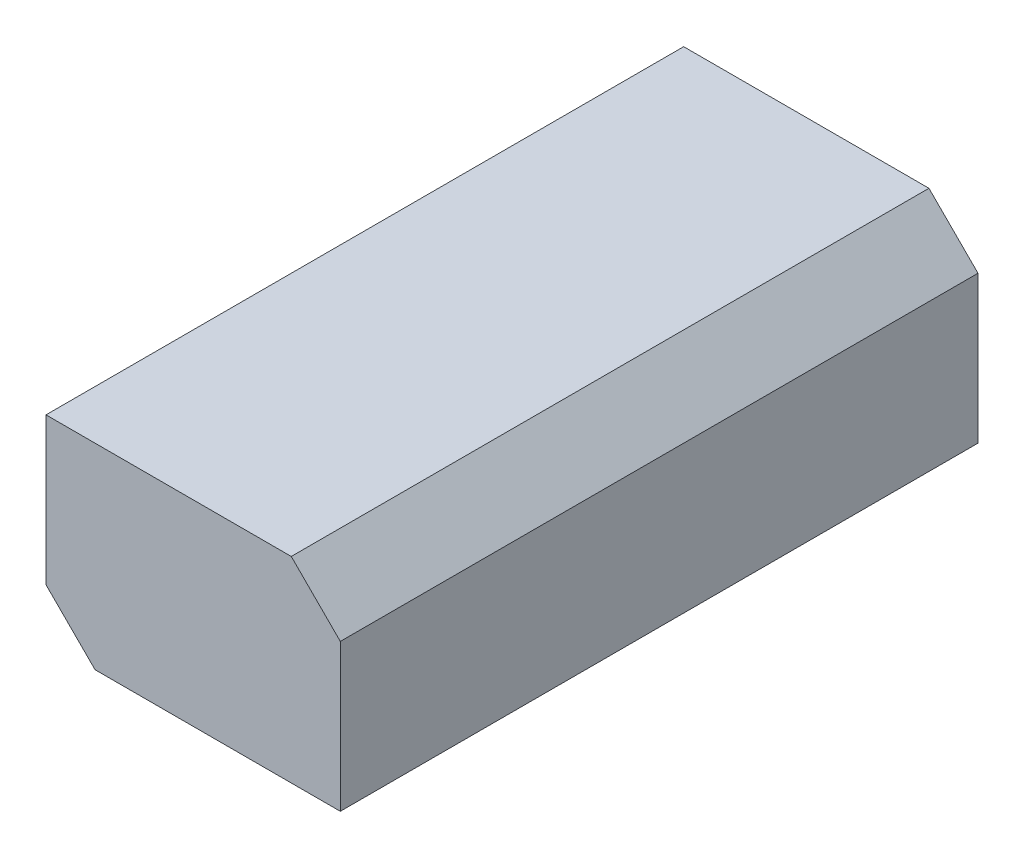
SolidWorks part; units mm, degrees
material "尼龙 101"
ref_plane "前视基准面" through (0, 0, 0) normal (0, 0, 1) x (1, 0, 0)
ref_plane "上视基准面" through (0, 0, 0) normal (0, 1, 0) x (1, 0, 0)
ref_plane "右视基准面" through (0, 0, 0) normal (1, 0, 0) x (0, 0, -1)
sketch "草图1" plane through (0, 0, 0) normal (0, 0, 1) x (1, 0, 0)
  line L1 (0, 0) -> (60, 0)
  line L2 (0, 0) -> (0, -40)
  line L3 (0, -40) -> (60, -40)
  line L4 (60, 0) -> (60, -40)
  dimension "D1" = 60
  dimension "D2" = 40
extrude "凸台-拉伸1" add sketch "草图1" along normal blind 130
chamfer "倒角1" distance 10 2 edges at (0, -40, 65) (60, 0, 65)
